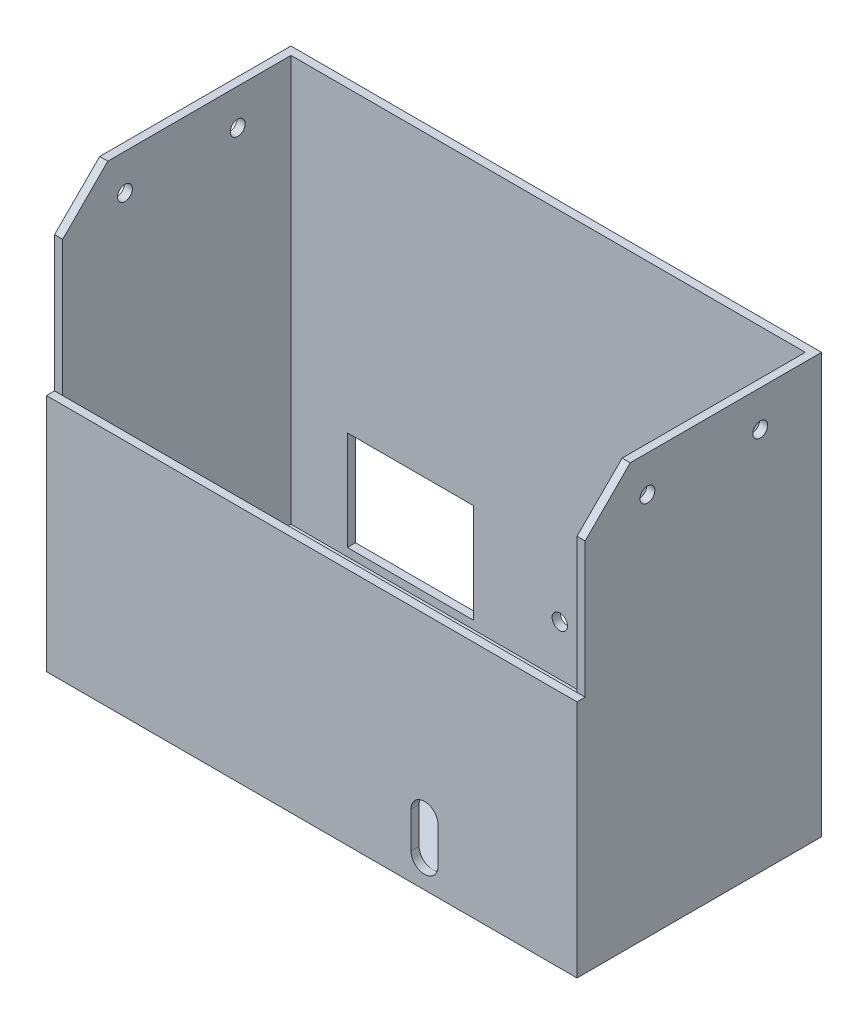
SolidWorks part; units mm, degrees
ref_plane "Front Plane" through (0, 0, 0) normal (0, 0, 1) x (1, 0, 0)
ref_plane "Top Plane" through (0, 0, 0) normal (0, 1, 0) x (1, 0, 0)
ref_plane "Right Plane" through (0, 0, 0) normal (1, 0, 0) x (0, 0, -1)
sketch "Sketch1" plane through (0, 0, 0) normal (0, 1, 0) x (1, 0, 0)
  line L1 (-56.8, 25.1) -> (56.8, 25.1) construction
  line L2 (-56.8, 25.1) -> (-56.8, -25.1) construction
  line L3 (-56.8, -25.1) -> (56.8, -25.1) construction
  line L4 (56.8, 25.1) -> (56.8, -25.1) construction
  line L5 (-56.8, 25.1) -> (56.8, -25.1) construction
  line L6 (-56.8, -25.1) -> (56.8, 25.1) construction
  point P0 (0, 0)
  dimension "D1" = 113.6
  dimension "D2" = 50.2
sketch "Sketch2" plane through (0, 0, 0) normal (0, 1, 0) x (1, 0, 0)
  line L21 (-58.8, -27.1) -> (58.8, -27.1)
  line L22 (58.8, -27.1) -> (58.8, 27.1)
  line L23 (-58.8, 27.1) -> (-58.8, -27.1)
  line L24 (58.8, 27.1) -> (-58.8, 27.1)
  line L25 (-58.8, -27.1) -> (58.8, -27.1)
  line L26 (58.8, -27.1) -> (58.8, 27.1)
  line L27 (-58.8, 27.1) -> (-58.8, -27.1)
  line L28 (58.8, 27.1) -> (-58.8, 27.1)
  dimension "D1" = 2
extrude "Boss-Extrude1" add sketch "Sketch2" along normal blind 3
sketch "Sketch3" plane through (0, 3, 0) normal (0, 1, 0) x (1, 0, 0)
  line L0 (-57, 25.3) -> (-57, -25.3)
  line L1 (-57, -25.3) -> (57, -25.3)
  line L2 (57, -25.3) -> (57, 25.3)
  line L3 (57, 25.3) -> (-57, 25.3)
  line L4 (-58.8, 27.1) -> (-58.8, -27.1)
  line L5 (-58.8, -27.1) -> (58.8, -27.1)
  line L6 (58.8, -27.1) -> (58.8, 27.1)
  line L7 (58.8, 27.1) -> (-58.8, 27.1)
  line L8 (-58.8, 27.1) -> (-58.8, -27.1)
  line L9 (-58.8, -27.1) -> (58.8, -27.1)
  line L10 (58.8, -27.1) -> (58.8, 27.1)
  line L11 (58.8, 27.1) -> (-58.8, 27.1)
  dimension "D1" = 0
  dimension "D2" = 1.8
extrude "Boss-Extrude2" add sketch "Sketch3" along normal blind 50
sketch "Sketch4" plane through (0, 53, 0) normal (0, 1, 0) x (1, 0, 0)
  line L0 (57, -25.3) -> (57, 25.3) construction
  line L1 (57, 25.3) -> (-57, 25.3) construction
  line L2 (-57, 25.3) -> (-57, -25.3) construction
  line L3 (57, -25.3) -> (57, 25.3)
  line L4 (58.8, 27.1) -> (-58.8, 27.1)
  line L5 (-58.8, 27.1) -> (-58.8, -27.1)
  line L6 (-58.8, -27.1) -> (58.8, -27.1)
  line L7 (58.8, -27.1) -> (58.8, 27.1)
  line L8 (58.8, 27.1) -> (-58.8, 27.1)
  line L9 (-58.8, 27.1) -> (-58.8, -25.3)
  line L11 (58.8, -25.3) -> (58.8, 27.1)
  line L12 (57, 25.3) -> (-57, 25.3)
  line L13 (-57, 25.3) -> (-57, -25.3)
  line L14 (57, -25.3) -> (58.8, -25.3)
  line L15 (-57, -25.3) -> (-58.8, -25.3)
  dimension "D1" = 0
extrude "Boss-Extrude3" add sketch "Sketch4" along normal blind 40
chamfer "Chamfer1" distance 10 angle 45 2 edges at (57.9, 93, 25.3) (-57.9, 93, 25.3)
sketch "Sketch5" plane through (-58.8, 0, 0) normal (-1, 0, 0) x (0, 0, 1)
  line L0 (25.3, 53) -> (27.1, 53) construction
  line L1 (-27.1, 93) -> (-27.1, 0) construction
  circle A0 centre (11.5, 85) radius 1.65
  circle A1 centre (-13.5, 85) radius 1.65
  dimension "D2" = 3.3
  dimension "D1" = 32
  dimension "D3" = 25
  dimension "D4" = 13.6
extrude "Cut-Extrude1" cut sketch "Sketch5" against normal through all
sketch "Sketch6" plane through (0, 0, -27.1) normal (0, 0, -1) x (-1, 0, 0)
  line L0 (-58.8, 0) -> (58.8, 0) construction
  line L1 (-39.4, 23.8) -> (-11.4, 23.8)
  line L2 (-39.4, 23.8) -> (-39.4, 4.2)
  line L3 (-39.4, 4.2) -> (-11.4, 4.2)
  line L4 (-11.4, 23.8) -> (-11.4, 4.2)
  line L5 (-39.4, 23.8) -> (-11.4, 4.2) construction
  line L6 (-39.4, 4.2) -> (-11.4, 23.8) construction
  line L7 (16.5, 26.8) -> (44.5, 26.8)
  line L8 (16.5, 26.8) -> (16.5, 4.8)
  line L9 (16.5, 4.8) -> (44.5, 4.8)
  line L10 (44.5, 26.8) -> (44.5, 4.8)
  line L11 (16.5, 26.8) -> (44.5, 4.8) construction
  line L12 (16.5, 4.8) -> (44.5, 26.8) construction
  line L14 (10.5, 3) -> (50.5, 3) construction
  circle A0 centre (-2.575, 14.075) radius 1.7
  circle A1 centre (-44.275, 14.075) radius 1.7
  point P0 (-25.4, 14)
  point P8 (30.5, 15.8)
  point P11 (0, 0)
  point P12 (30.5, 3)
  dimension "D9" = 3.4
  dimension "D10" = 3.4
  dimension "D1" = 19.6
  dimension "D2" = 28
  dimension "D3" = 25.4
  dimension "D4" = 4.2
  dimension "D5" = 4.8
  dimension "D6" = 22
  dimension "D7" = 28
  dimension "D8" = 40
extrude "Cut-Extrude2" cut sketch "Sketch6" against normal up to next
sketch "Sketch7" plane through (0, 0, 27.1) normal (0, 0, 1) x (1, 0, 0)
  line L0 (25, 6) -> (25, 14) construction
  line L1 (22, 6) -> (22, 14)
  line L2 (28, 6) -> (28, 14)
  line L4 (-58.8, 0) -> (58.8, 0) construction
  arc A0 (22, 6) -> (28, 6) centre (25, 6) ccw
  arc A1 (28, 14) -> (22, 14) centre (25, 14) ccw
  point P2 (25, 10)
  dimension "D2" = 3
  dimension "D1" = 8
  dimension "D3" = 25
  dimension "D4" = 6
extrude "Cut-Extrude3" cut sketch "Sketch7" against normal up to next
